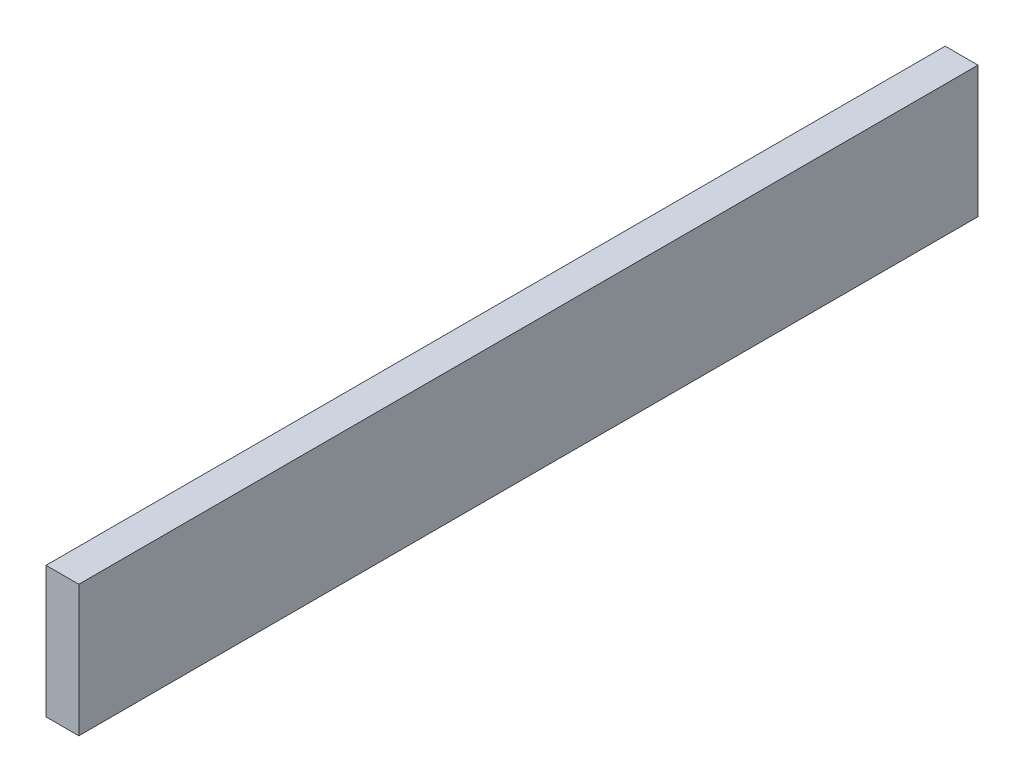
SolidWorks part; units mm, degrees
ref_plane "Front Plane" through (0, 0, 0) normal (0, 0, 1) x (1, 0, 0)
ref_plane "Top Plane" through (0, 0, 0) normal (0, 1, 0) x (1, 0, 0)
ref_plane "Right Plane" through (0, 0, 0) normal (1, 0, 0) x (0, 0, -1)
sketch "Sketch1" plane through (0, 0, 0) normal (0, 0, 1) x (1, 0, 0)
  line L1 (0, 0) -> (6.35, 0)
  line L2 (0, 0) -> (0, 25.4)
  line L3 (0, 25.4) -> (6.35, 25.4)
  line L4 (6.35, 0) -> (6.35, 25.4)
  dimension "D1" = 6.35
  dimension "D2" = 25.4
extrude "Boss-Extrude1" add sketch "Sketch1" along normal blind 173.99
